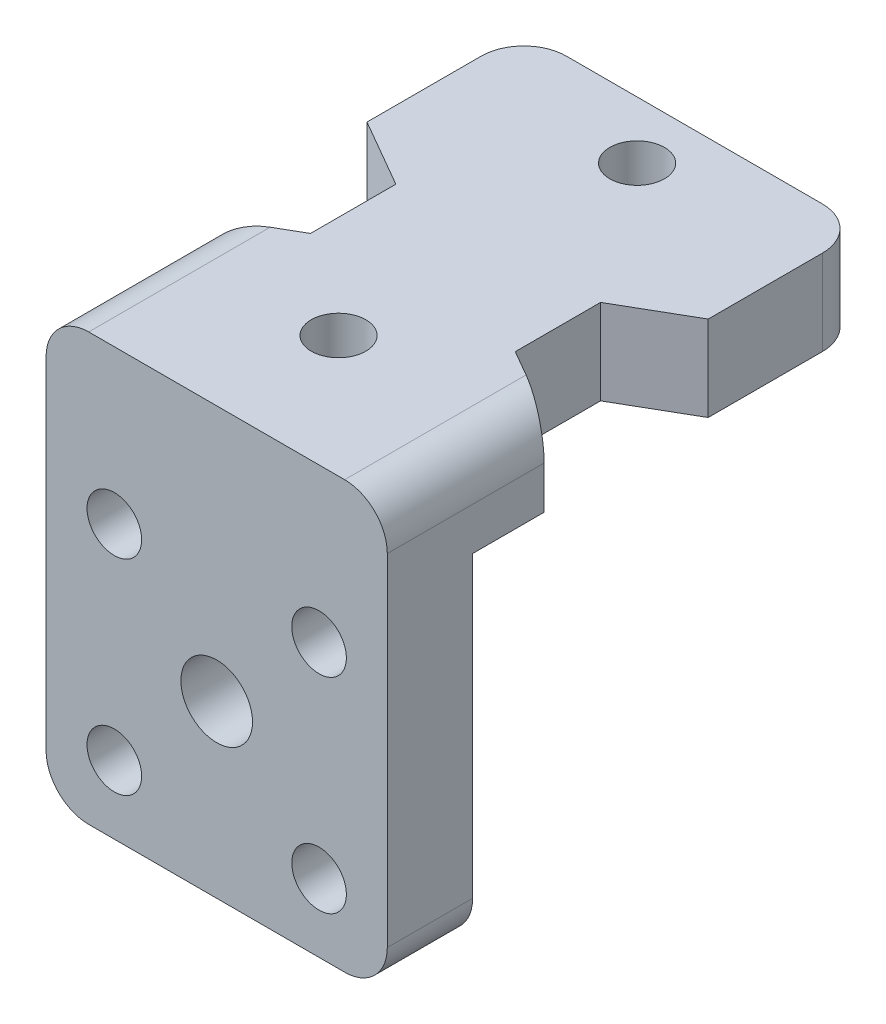
SolidWorks part; units mm, degrees
ref_plane "Front Plane" through (0, 0, 0) normal (0, 0, 1) x (1, 0, 0)
ref_plane "Top Plane" through (0, 0, 0) normal (0, 1, 0) x (1, 0, 0)
ref_plane "Right Plane" through (0, 0, 0) normal (1, 0, 0) x (0, 0, -1)
sketch "Sketch2" plane through (0, 0, 0) normal (0, 0, 1) x (1, 0, 0)
  line L0 (-5.8609, 5.8609) -> (5.8609, 5.8609) construction
  line L1 (-10, -10) -> (10, -10)
  line L2 (-10, -10) -> (-10, 10)
  line L3 (-10, 10) -> (10, 10)
  line L4 (10, -10) -> (10, 10)
  line L5 (-5.8609, 5.8609) -> (-5.8609, -5.8609) construction
  line L6 (-5.8609, -5.8609) -> (5.8609, -5.8609) construction
  line L7 (5.8609, -5.8609) -> (5.8609, 5.8609) construction
  point P0 (0, 0)
  dimension "D1" = 20
  dimension "D2" = 20
extrude "Boss-Extrude1" add sketch "Sketch2" along normal blind 5
sketch "Sketch3" plane through (0, 0, 5) normal (0, 0, 1) x (1, 0, 0)
  circle A0 centre (0, 0) radius 2.1
  dimension "D1" = 4.2
extrude "Cut-Extrude1" cut sketch "Sketch3" against normal blind 5
fillet "Fillet2" radius 2.5 2 edges at (10, -10, 2.5) (-10, -10, 2.5)
sketch "Sketch5" plane through (0, 10, 0) normal (0, 1, 0) x (1, 0, 0)
  line L0 (0, -5) -> (0, 19.6415) construction
  line L1 (-10, -5) -> (10, -5)
  line L2 (-10, -5) -> (-10, 4.1906)
  line L3 (-10, 23) -> (10, 23)
  line L4 (10, -5) -> (10, 4.1906)
  line L5 (-10, 13.8094) -> (-6, 11.5)
  line L6 (-6, 11.5) -> (-6, 6.5)
  line L7 (-6, 6.5) -> (-10, 4.1906)
  line L8 (-10, 9) -> (10, 9) construction
  line L9 (-6, 9) -> (-4.7034, 9) construction
  line L10 (-4.7034, 9) -> (-7.5109, 9) construction
  line L11 (6, 6.5) -> (10, 4.1906)
  line L12 (10, 13.8094) -> (6, 11.5)
  line L13 (6, 11.5) -> (6, 6.5)
  line L14 (10, 13.8094) -> (10, 23)
  line L15 (-10, 13.8094) -> (-10, 23)
  circle A0 centre (0, 2.1415) radius 1.6
  circle A1 centre (0, 19.6415) radius 1.6
  dimension "D3" = 3.2
  dimension "D4" = 3.2
  dimension "D6" = 120
  dimension "D1" = 20
  dimension "D2" = 28
  dimension "D5" = 17.5
  dimension "D7" = 120
  dimension "D8" = 4
  dimension "D9" = 5
extrude "Boss-Extrude2" add sketch "Sketch5" along normal blind 5
fillet "Fillet4" radius 2.5 4 edges at (-10, 15, 0.4047) (10, 15, 0.4047) (10, 12.5, -23) (-10, 12.5, -23)
sketch "Sketch6" plane through (0, 0, 0) normal (0, 0, -1) x (-1, 0, 0)
  line L6 (-6, -6) -> (6, -6) construction
  line L7 (-6, -6) -> (-6, 6) construction
  line L8 (-6, 6) -> (6, 6) construction
  line L9 (6, -6) -> (6, 6) construction
  line L10 (-6, -6) -> (6, 6) construction
  line L11 (-6, 6) -> (6, -6) construction
  circle A2 centre (-6, 6) radius 1.6
  circle A3 centre (6, 6) radius 1.6
  circle A4 centre (6, -6) radius 1.6
  circle A5 centre (-6, -6) radius 1.6
  point P5 (0, 0)
  dimension "D3" = 3.2
  dimension "D4" = 3.2
  dimension "D5" = 3.2
  dimension "D6" = 3.2
  dimension "D1" = 12
  dimension "D2" = 12
extrude "Cut-Extrude2" cut sketch "Sketch6" against normal blind 10
